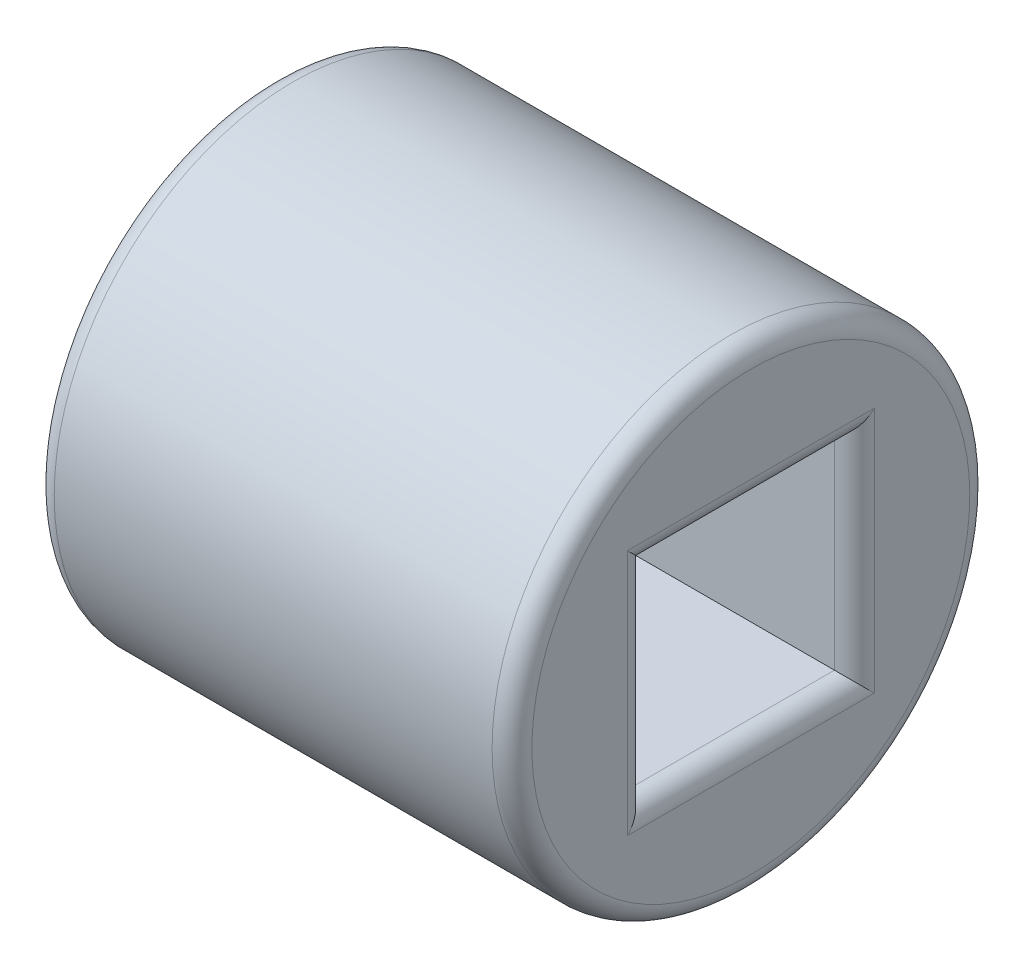
SolidWorks part; units mm, degrees
ref_plane "Front Plane" through (0, 0, 0) normal (0, 0, 1) x (1, 0, 0)
ref_plane "Top Plane" through (0, 0, 0) normal (0, 1, 0) x (1, 0, 0)
ref_plane "Right Plane" through (0, 0, 0) normal (1, 0, 0) x (0, 0, -1)
sketch "Sketch1" plane through (0, 0, 0) normal (1, 0, 0) x (0, 0, -1)
  line L1 (-3.302, 3.302) -> (3.302, 3.302)
  line L2 (-3.302, 3.302) -> (-3.302, -3.302)
  line L3 (-3.302, -3.302) -> (3.302, -3.302)
  line L4 (3.302, 3.302) -> (3.302, -3.302)
  line L5 (-3.302, 3.302) -> (3.302, -3.302) construction
  line L6 (-3.302, -3.302) -> (3.302, 3.302) construction
  circle A0 centre (0, 0) radius 7.62
  dimension "D2" = 15.24
  dimension "D1" = 6.604
extrude "Boss-Extrude1" add sketch "Sketch1" along normal blind 15.24
fillet "Fillet1" radius 0.635 10 edges at (0, -3.302, 0) (0, 0, 3.302) (0, 3.302, 0) (0, 0, -3.302) (0, 0, -7.62) (15.24, 0, 3.302) (15.24, -3.302, 0) (15.24, 0, -3.302) (15.24, 3.302, 0) (15.24, 0, -7.62)
